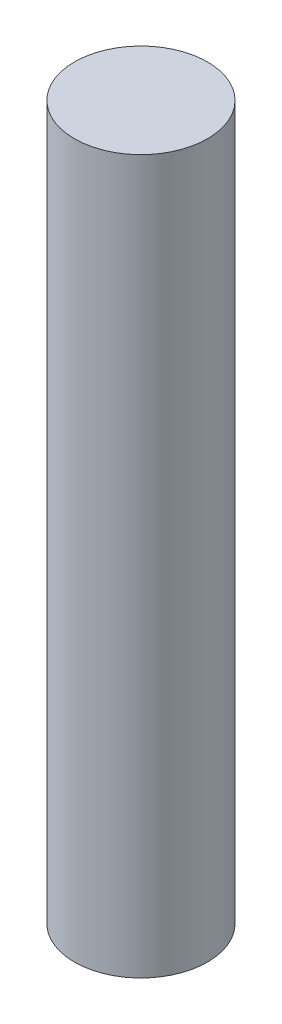
SolidWorks part; units mm, degrees
ref_plane "Front Plane" through (0, 0, 0) normal (0, 0, 1) x (1, 0, 0)
ref_plane "Top Plane" through (0, 0, 0) normal (0, 1, 0) x (1, 0, 0)
ref_plane "Right Plane" through (0, 0, 0) normal (1, 0, 0) x (0, 0, -1)
sketch "Sketch1" plane through (0, 0, 0) normal (0, 1, 0) x (1, 0, 0)
  circle A0 centre (0, 0) radius 10.668
  dimension "D1" = 21.336
extrude "Boss-Extrude1" add sketch "Sketch1" along normal blind 114.3
